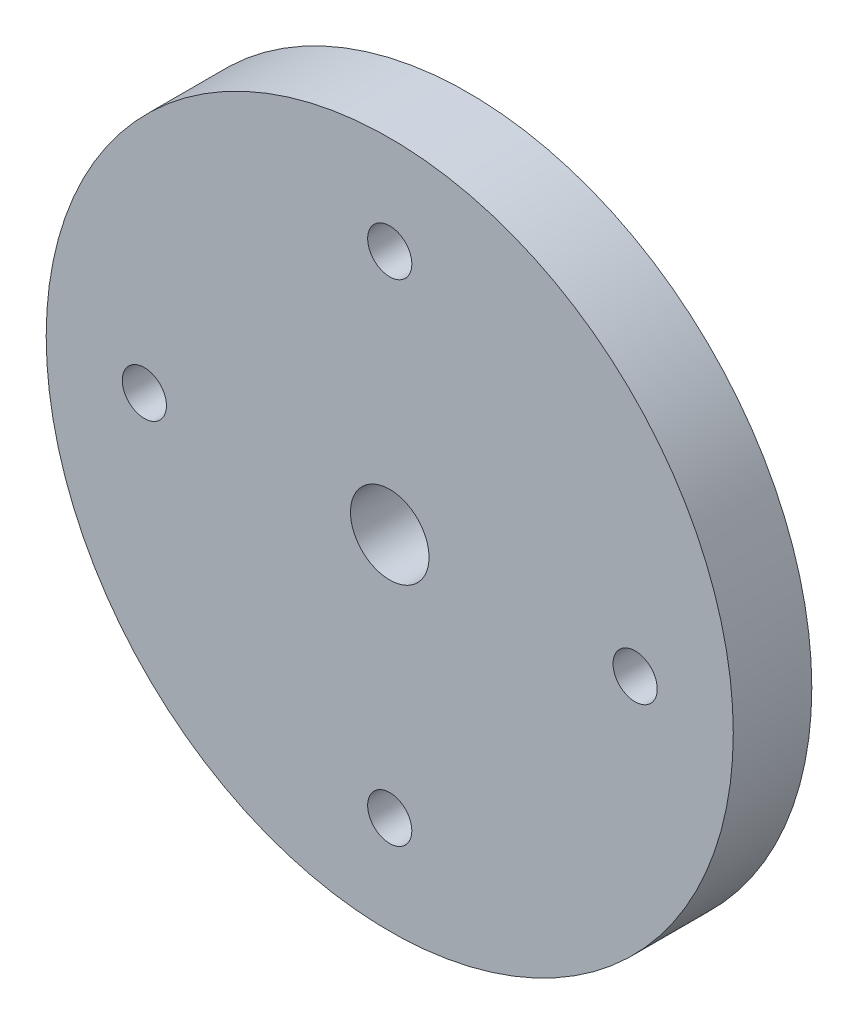
SolidWorks part; units mm, degrees
ref_plane "前视基准面" through (0, 0, 0) normal (0, 0, 1) x (1, 0, 0)
ref_plane "上视基准面" through (0, 0, 0) normal (0, 1, 0) x (1, 0, 0)
ref_plane "右视基准面" through (0, 0, 0) normal (1, 0, 0) x (0, 0, -1)
other "Configuration Table"
sketch "外形与孔位_gripper_adapter" plane through (0, 0, 0) normal (0, 0, 1) x (1, 0, 0)
  circle A0 centre (35, 35) radius 35
  circle A1 centre (35, 35) radius 4
  circle A2 centre (60, 35) radius 2.25
  circle A3 centre (35, 60) radius 2.25
  circle A4 centre (10, 35) radius 2.25
  circle A5 centre (35, 10) radius 2.25
extrude "板厚_8mm" add sketch "外形与孔位_gripper_adapter" along normal blind 8
